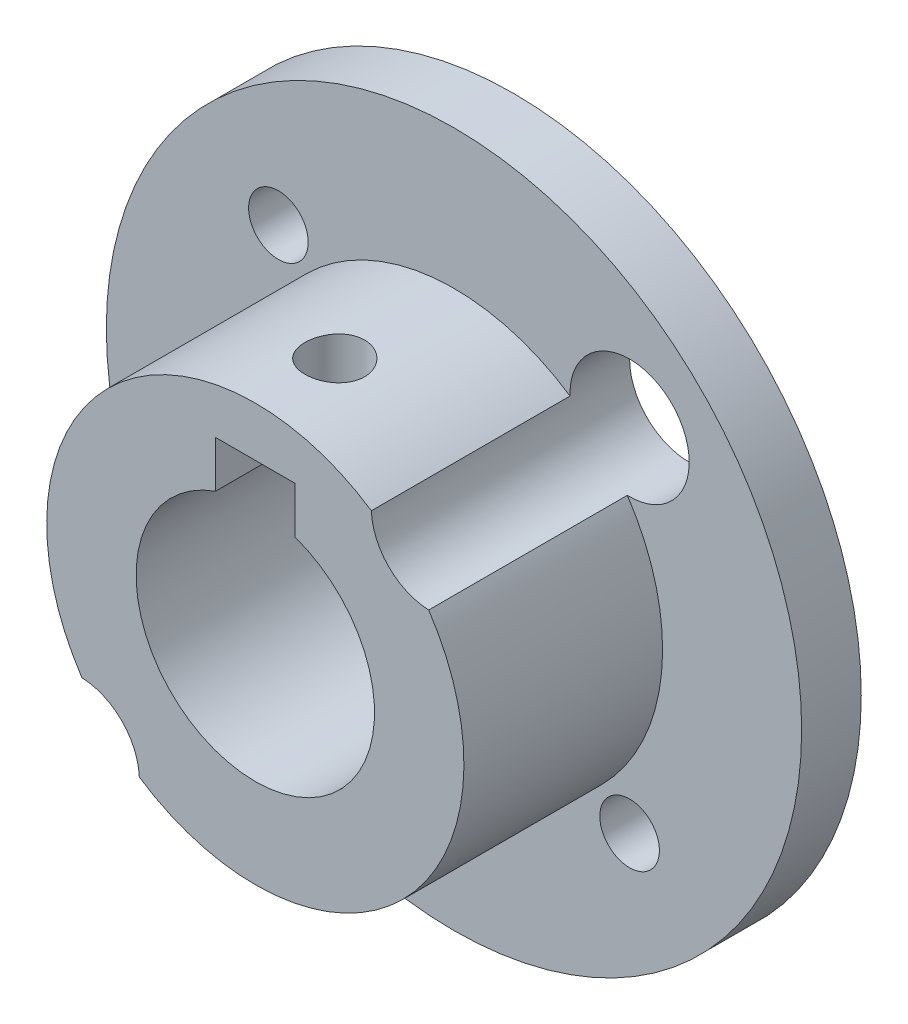
SolidWorks part; units mm, degrees
ref_plane "前视基准面" through (0, 0, 0) normal (0, 0, 1) x (1, 0, 0)
ref_plane "上视基准面" through (0, 0, 0) normal (0, 1, 0) x (1, 0, 0)
ref_plane "右视基准面" through (0, 0, 0) normal (1, 0, 0) x (0, 0, -1)
sketch "草图1" plane through (0, 0, 0) normal (0, 0, 1) x (1, 0, 0)
  line L0 (0, 0) -> (0, 14.1073) construction
  line L1 (0, 0) -> (19.7681, 0) construction
  line L3 (-2, 8) -> (2, 8)
  line L4 (-2, 8) -> (-2, 5.6569)
  line L6 (2, 8) -> (2, 5.6569)
  circle A0 centre (0, 0) radius 10.5
  arc A1 (-2, 5.6569) -> (2, 5.6569) centre (0, 0) ccw
  dimension "D1" = 21
  dimension "D2" = 12
  dimension "D4" = 8
  dimension "D3" = 4
extrude "拉伸1" add sketch "草图1" along normal blind 10
sketch "草图3" plane through (0, 0, 0) normal (0, 0, -1) x (-1, 0, 0)
  line L0 (2, 8) -> (2, 5.6569) construction
  line L1 (-2, 8) -> (2, 8) construction
  line L2 (-2, 5.6569) -> (-2, 8) construction
  line L3 (2, 8) -> (2, 5.6569)
  line L4 (-2, 8) -> (2, 8)
  line L5 (-2, 5.6569) -> (-2, 8)
  circle A0 centre (0, 0) radius 17.5
  arc A1 (-2, 5.6569) -> (2, 5.6569) centre (0, 0) ccw construction
  arc A2 (-2, 5.6569) -> (2, 5.6569) centre (0, 0) ccw
  dimension "D1" = 35
extrude "凸台-拉伸1" add sketch "草图3" along normal blind 3
sketch "草图4" plane through (0, 0, -3) normal (0, 0, -1) x (-1, 0, 0)
  line L0 (0, 0) -> (11.8931, 0) construction
  line L1 (0, 0) -> (-12.0688, 12.0688) construction
  line L2 (0, 0) -> (10.976, 10.976) construction
  circle A0 centre (0, 0) radius 12.5 construction
  circle A1 centre (8.8388, 8.8388) radius 1.5
  circle A2 centre (-8.8388, 8.8388) radius 3
  circle A3 centre (8.8388, -8.8388) radius 3
  circle A4 centre (-8.8388, -8.8388) radius 1.5
  dimension "D2" = 25
  dimension "D3" = 3
  dimension "D4" = 6
  dimension "D1" = 45
extrude "切除-拉伸1" cut sketch "草图4" against normal through all
sketch "草图5" plane through (0, 8, 0) normal (0, -1, 0) x (1, 0, 0)
  line L0 (0, 0) -> (0, 12) construction
  line L1 (5.841, 10) -> (-10.5, 10) construction
  circle A0 centre (0, 6) radius 1.5
  dimension "D1" = 3
  dimension "D2" = 4
extrude "切除-拉伸2" cut sketch "草图5" against normal up to next
